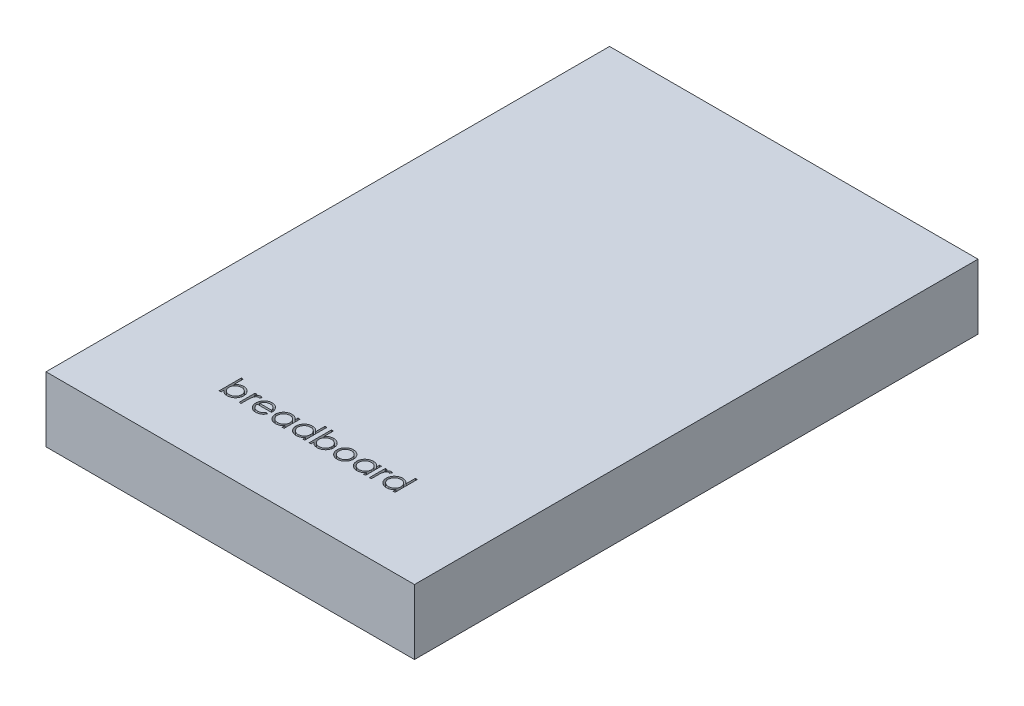
SolidWorks part; units mm, degrees
ref_plane "Front Plane" through (0, 0, 0) normal (0, 0, 1) x (1, 0, 0)
ref_plane "Top Plane" through (0, 0, 0) normal (0, 1, 0) x (1, 0, 0)
ref_plane "Right Plane" through (0, 0, 0) normal (1, 0, 0) x (0, 0, -1)
sketch "Sketch1" plane through (0, 0, 0) normal (0, 1, 0) x (1, 0, 0)
  line L1 (0, 0) -> (53.975, 0)
  line L2 (0, 0) -> (0, 82.55)
  line L3 (0, 82.55) -> (53.975, 82.55)
  line L4 (53.975, 0) -> (53.975, 82.55)
  dimension "D1" = 82.55
  dimension "D2" = 53.975
extrude "Boss-Extrude1" add sketch "Sketch1" along normal blind 9.525
sketch "Sketch2" plane through (0, 9.525, 0) normal (0, 1, 0) x (1, 0, 0)
  text T0 "breadboard"
extrude "Cut-Extrude1" cut sketch "Sketch2" against normal blind 1.905
